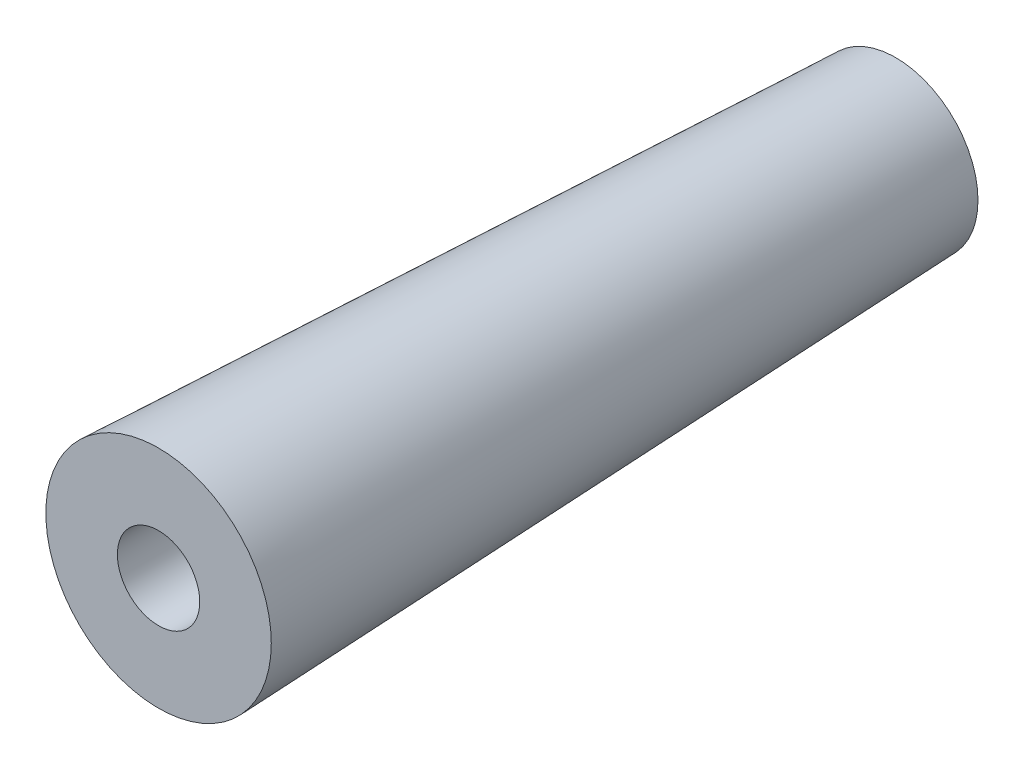
SolidWorks part; units mm, degrees
material "PW50:33:Sc:0:Re:14:"
ref_plane "Plane1" through (0, 0, 0) normal (0, 0, 1) x (1, 0, 0)
ref_plane "Plane2" through (0, 0, 0) normal (0, 1, 0) x (1, 0, 0)
ref_plane "Plane3" through (0, 0, 0) normal (1, 0, 0) x (0, 0, -1)
other "Configuration Table"
sketch "Sketch1" plane through (0, 0, 0) normal (0, 0, 1) x (1, 0, 0)
  circle A0 centre (0, 0) radius 9.5
  dimension "D1" = 19
ref_plane "Plane4" through (0, 0, 85) normal (0, 0, 1) x (1, 0, 0)
sketch "Sketch2" plane through (0, 0, 85) normal (0, 0, 1) x (1, 0, 0)
  circle A0 centre (0, 0) radius 13
  dimension "D1" = 26
loft "Base-Loft" add profiles "Sketch1", "Sketch2"
sketch "Sketch3" plane through (0, 0, 85) normal (0, 0, 1) x (1, 0, 0)
  circle A0 centre (0, 0) radius 4.75
  dimension "D1" = 9.5
extrude "Cut-Extrude1" cut sketch "Sketch3" against normal through all
